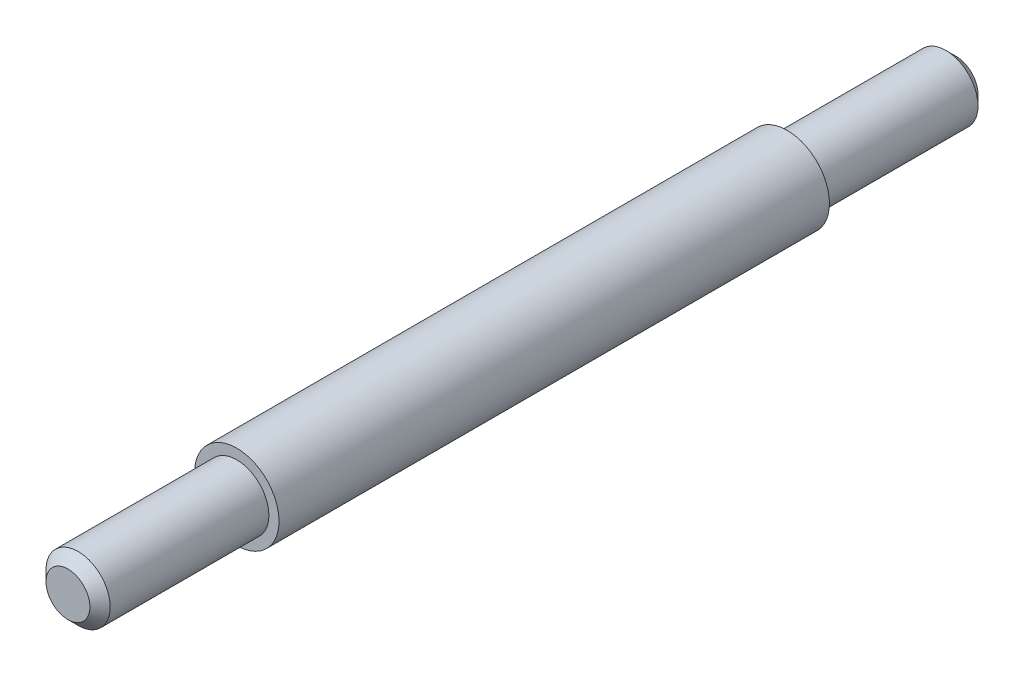
SolidWorks part; units mm, degrees
ref_plane "Front Plane" through (0, 0, 0) normal (0, 0, 1) x (1, 0, 0)
ref_plane "Top Plane" through (0, 0, 0) normal (0, 1, 0) x (1, 0, 0)
ref_plane "Right Plane" through (0, 0, 0) normal (1, 0, 0) x (0, 0, -1)
sketch "Sketch1" plane through (0, 0, 0) normal (0, 0, 1) x (1, 0, 0)
  circle A0 centre (0, 0) radius 0.125
  dimension "D1" = 0.25
extrude "Boss-Extrude1" add sketch "Sketch1" along normal blind 1.63
sketch "Sketch2" plane through (0, 0, 0) normal (0, 0, 1) x (1, 0, 0)
  circle A0 centre (0, 0) radius 0.095
  dimension "D1" = 0.19
extrude "Boss-Extrude2" add sketch "Sketch2" against normal blind 0.5
sketch "Sketch3" plane through (0, 0, 1.63) normal (0, 0, 1) x (1, 0, 0)
  circle A1 centre (0, 0) radius 0.095
  dimension "D1" = 0.19
extrude "Boss-Extrude3" add sketch "Sketch3" along normal blind 0.5
chamfer "Chamfer1" distance 0.03 angle 45 1 edges at (0.095, 0, -0.5)
fillet "Chamfer2" radius 0.03 1 edges at (0.095, 0, 2.13) profile chamfer
